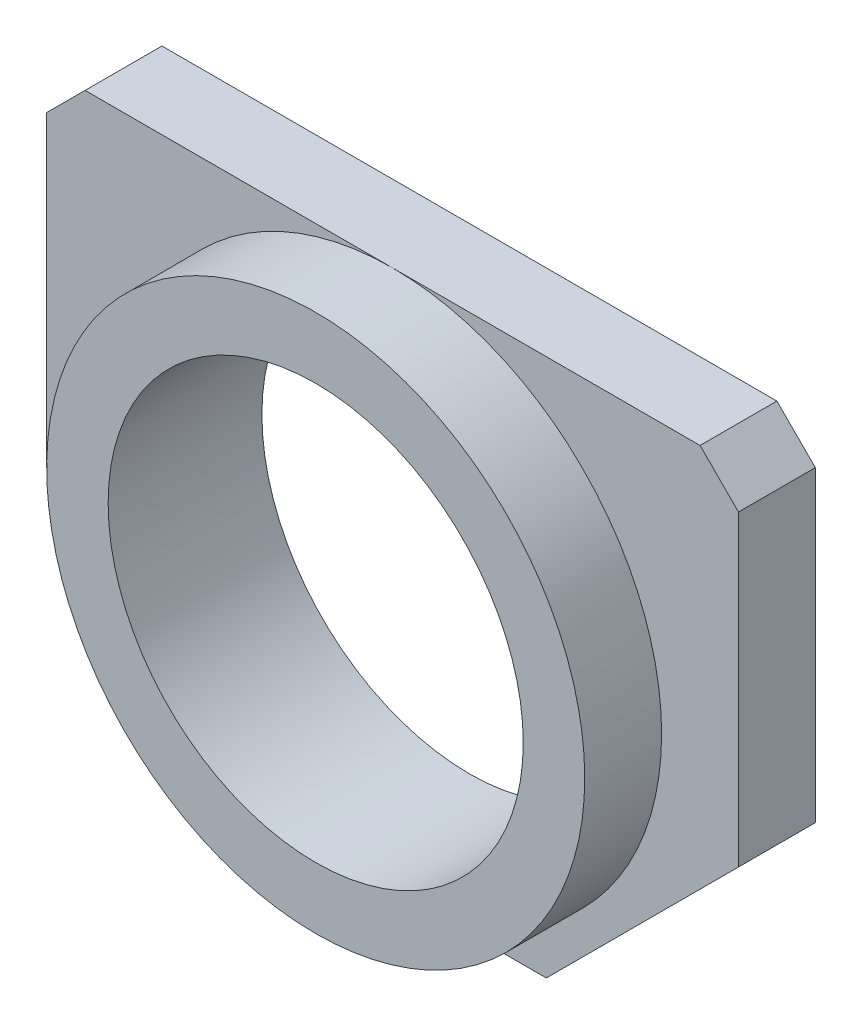
SolidWorks part; units mm, degrees
ref_plane "Front Plane" through (0, 0, 0) normal (0, 0, 1) x (1, 0, 0)
ref_plane "Top Plane" through (0, 0, 0) normal (0, 1, 0) x (1, 0, 0)
ref_plane "Right Plane" through (0, 0, 0) normal (1, 0, 0) x (0, 0, -1)
sketch "Sketch1" plane through (0, 0, 0) normal (0, 0, 1) x (1, 0, 0)
  line L1 (-9, -7) -> (9, -7)
  line L2 (-9, -7) -> (-9, 7)
  line L3 (-9, 7) -> (9, 7)
  line L4 (9, -7) -> (9, 7)
  line L5 (-9, -7) -> (9, 7) construction
  line L6 (-9, 7) -> (9, -7) construction
  point P0 (0, 0)
  dimension "D1" = 18
  dimension "D2" = 14
extrude "Boss-Extrude1" add sketch "Sketch1" along normal blind 2
sketch "Sketch2" plane through (0, 0, 2) normal (0, 0, 1) x (1, 0, 0)
  line L0 (9, 7) -> (-9, 7) construction
  circle A0 centre (0, 0) radius 7
  dimension "D1" = 7
  dimension "D2" = 14
extrude "Boss-Extrude2" add sketch "Sketch2" along normal blind 2
hole_wizard "M12x1.25 Tapped Hole1" positions "Sketch6" profile "Sketch5" tap size "M12x1.25" standard "Ansi Metric"
sketch "Sketch6" plane through (0, 0, 4) normal (0, 0, 1) x (1, 0, 0)
  point P0 (0, 0)
sketch "Sketch5" plane through (0, 0, 4) normal (1, 0, 0) x (0, -1, 0)
  line L0 (0, 0) -> (0, 11.9946)
  line L1 (0, 11.9946) -> (5.4, 8.75)
  line L2 (5.4, 8.75) -> (5.4, 0)
  line L5 (5.4, 0) -> (0, 0)
  line L10 (0, 11.9946) -> (-5.4, 8.75) construction
  line L11 (0, -6.35) -> (0, 107.95) construction
  dimension "Tap Drill Dia." = 10.8
  dimension "Tap Drill Depth" = 8.75
  dimension "Drill Angle" = 118
cosmetic thread "Hole Thread1" parameters "D1"=4, "D2"=12
chamfer "Chamfer6" distance 5 angle 45 2 edges at (9, -7, 1) (-9, -7, 1)
chamfer "Chamfer7" distance 1 angle 45 2 edges at (9, 7, 1) (-9, 7, 1)
